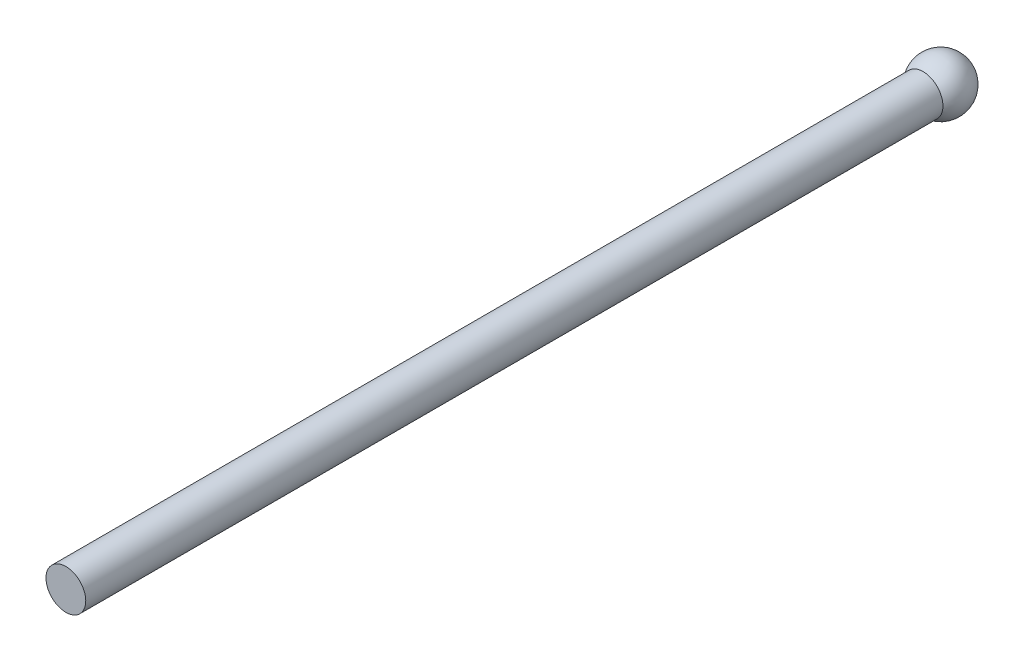
SolidWorks part; units mm, degrees
ref_plane "Front Plane" through (0, 0, 0) normal (0, 0, 1) x (1, 0, 0)
ref_plane "Top Plane" through (0, 0, 0) normal (0, 1, 0) x (1, 0, 0)
ref_plane "Right Plane" through (0, 0, 0) normal (1, 0, 0) x (0, 0, -1)
sketch "Sketch1" plane through (0, 0, 0) normal (0, 0, 1) x (1, 0, 0)
  circle A0 centre (0, 0) radius 7.5
  dimension "D1" = 15
extrude "Boss-Extrude1" add sketch "Sketch1" along normal blind 330 contours A0
sketch "Sketch2" plane through (0, 0, 0) normal (0, 1, 0) x (1, 0, 0)
  line L0 (0, 0) -> (0, 35.2643) construction
  line L2 (-7.5, 0) -> (-7.5, -330) construction
  line L4 (-7.5, -6.6144) -> (0, -6.6144)
  line L5 (0, -6.6144) -> (0, 10)
  arc A0 (-7.5, -6.6144) -> (0, 10) centre (0, 0) cw
  point P9 (-9.1144, 4.1144)
  dimension "D1" = 10
revolve "Revolve1" add sketch "Sketch2" angle 360 about L0
